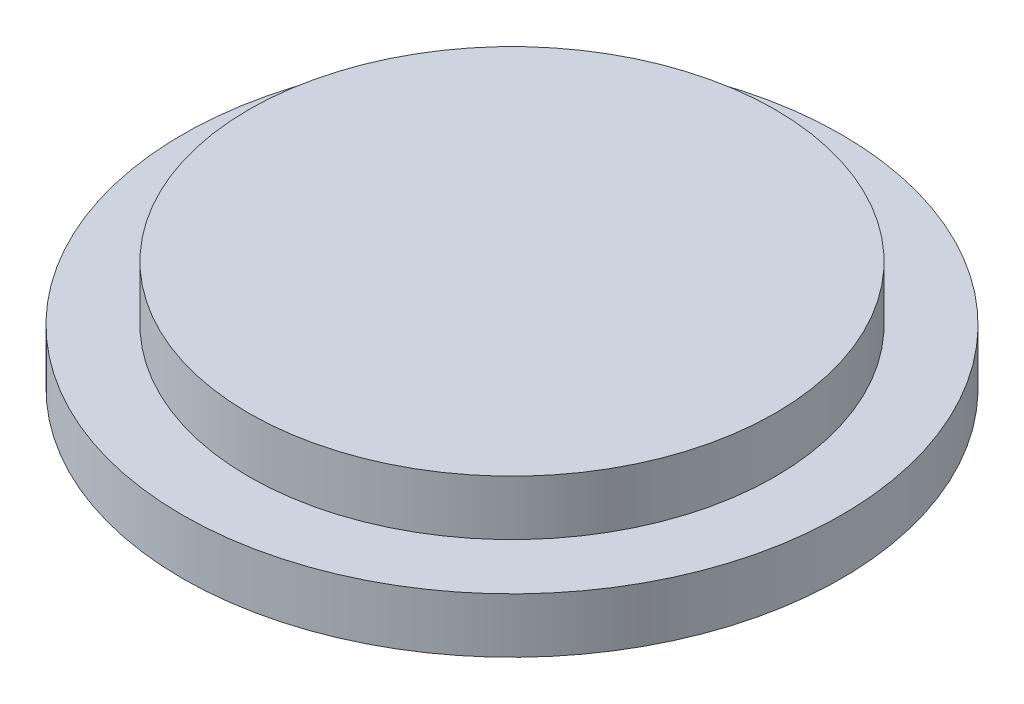
SolidWorks part; units mm, degrees
ref_plane "Plan de face" through (0, 0, 0) normal (0, 0, 1) x (1, 0, 0)
ref_plane "Plan de dessus" through (0, 0, 0) normal (0, 1, 0) x (1, 0, 0)
ref_plane "Plan de droite" through (0, 0, 0) normal (1, 0, 0) x (0, 0, -1)
sketch "Esquisse1" plane through (0, 0, 0) normal (0, 1, 0) x (1, 0, 0)
  circle A0 centre (0, 0) radius 47.9
  dimension "D1" = 95.8
extrude "Boss.-Extru.1" add sketch "Esquisse1" along normal blind 10
sketch "Esquisse2" plane through (0, 0, 0) normal (0, -1, 0) x (1, 0, 0)
  circle A0 centre (0, 0) radius 60
extrude "Boss.-Extru.2" add sketch "Esquisse2" along normal blind 10
